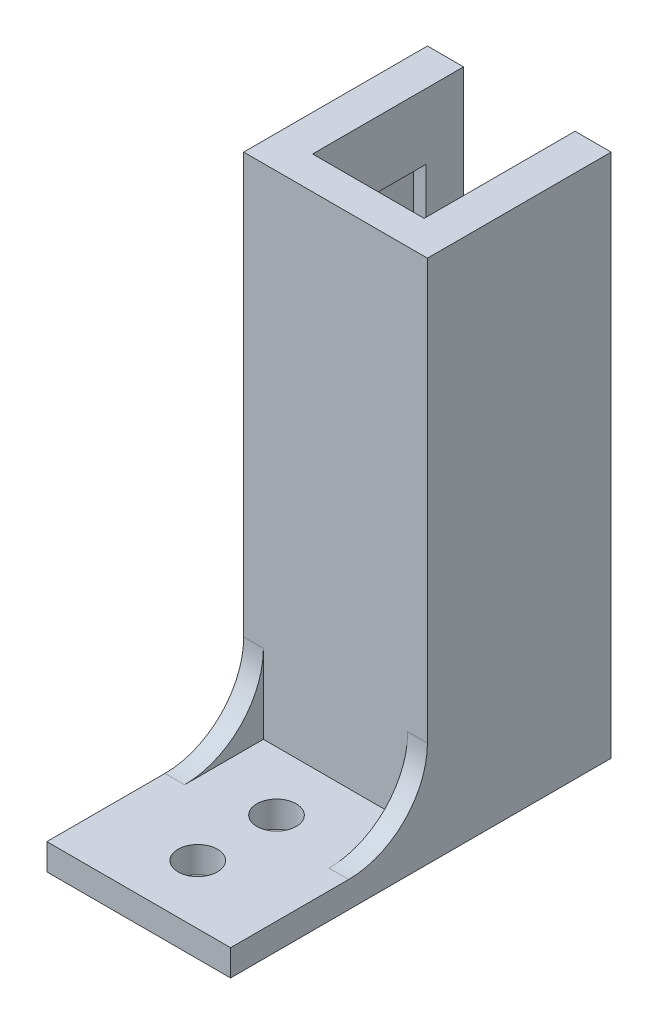
SolidWorks part; units mm, degrees
ref_plane "Front Plane" through (0, 0, 0) normal (0, 0, 1) x (1, 0, 0)
ref_plane "Top Plane" through (0, 0, 0) normal (0, 1, 0) x (1, 0, 0)
ref_plane "Right Plane" through (0, 0, 0) normal (1, 0, 0) x (0, 0, -1)
sketch "Sketch1" plane through (0, 0, 0) normal (0, 0, 1) x (1, 0, 0)
  line L1 (7, 20) -> (-7, 20)
  line L2 (7, 20) -> (7, -20)
  line L3 (7, -20) -> (-7, -20)
  line L4 (-7, 20) -> (-7, -20)
  line L5 (7, 20) -> (-7, -20) construction
  line L6 (7, -20) -> (-7, 20) construction
  point P0 (0, 0)
  dimension "D1" = 14
  dimension "D2" = 40
extrude "Boss-Extrude1" add sketch "Sketch1" along normal blind 14
sketch "Sketch2" plane through (0, -20, 0) normal (0, -1, 0) x (1, 0, 0)
  line L1 (5.2, 2.85) -> (-5.2, 2.85)
  line L2 (5.2, 2.85) -> (5.2, 11.5)
  line L3 (5.2, 11.5) -> (-5.2, 11.5)
  line L4 (-5.2, 2.85) -> (-5.2, 11.5)
  line L8 (4.25, 2.85) -> (-4.25, 2.85)
  line L9 (4.25, 2.85) -> (4.25, 0)
  line L10 (4.25, 0) -> (-4.25, 0)
  line L11 (-4.25, 2.85) -> (-4.25, 0)
  point P4 (0, 2.85)
  point P16 (0, 0)
  dimension "D1" = 11.5
  dimension "D2" = 8.65
  dimension "D3" = 10.4
  dimension "D4" = 8.5
extrude "Cut-Extrude1" cut sketch "Sketch2" against normal blind 35
sketch "Sketch3" plane through (0, -20, 0) normal (0, -1, 0) x (1, 0, 0)
  line L0 (0, 18.5) -> (0, 24.5) construction
  line L1 (7, 14) -> (-7, 14)
  line L2 (7, 14) -> (7, 29)
  line L3 (7, 29) -> (-7, 29)
  line L4 (-7, 14) -> (-7, 29)
  circle A0 centre (0, 18.5) radius 1.5
  circle A1 centre (0, 24.5) radius 1.5
  point P10 (0, 21.5)
  point P11 (-7, 21.5)
  point P15 (0, 14)
  dimension "D1" = 3
  dimension "D2" = 6
  dimension "D3" = 4.5
extrude "Boss-Extrude2" add sketch "Sketch3" against normal blind 2
sketch "Sketch4" plane through (-7, 0, 0) normal (-1, 0, 0) x (0, 0, 1)
  line L1 (29, -18) -> (14, -18) construction
  line L2 (14, 20) -> (14, -18) construction
  line L3 (14, -12) -> (14, -18)
  line L4 (14, -18) -> (20, -18)
  arc A0 (20, -18) -> (14, -12) centre (20, -12) cw
  dimension "D1" = 6
extrude "Boss-Extrude3" add sketch "Sketch4" against normal blind 1.5
mirror "Mirror1" about plane through (0, 0, 0) normal (1, 0, 0) of "Boss-Extrude3"
sketch "Sketch5" plane through (0, 15, 0) normal (0, -1, 0) x (1, 0, 0)
  line L0 (5.2, 11.5) -> (-5.2, 11.5) construction
  line L1 (4.25, 0) -> (-4.25, 0)
  line L2 (4.25, 0) -> (4.25, 11.5)
  line L3 (4.25, 11.5) -> (-4.25, 11.5)
  line L4 (-4.25, 0) -> (-4.25, 11.5)
  line L5 (7, 0) -> (4.25, 0) construction
  line L6 (-4.25, 0) -> (4.25, 0) construction
extrude "Cut-Extrude2" cut sketch "Sketch5" against normal through all
sketch "Sketch6" plane through (0, 0, 0) normal (0, 0, -1) x (-1, 0, 0)
  line L0 (-7, 20) -> (-7, -20) construction
  line L1 (-7, 0) -> (7, 0)
  line L2 (-7, 0) -> (-7, -20)
  line L3 (-7, -20) -> (7, -20)
  line L4 (7, 0) -> (7, -20)
extrude "Cut-Extrude3" [suppressed] cut sketch "Sketch6" against normal through all
sketch "Sketch7" plane through (0, -20, 0) normal (0, -1, 0) x (1, 0, 0)
  line L0 (5.2, 2.85) -> (4.25, 2.85)
  line L1 (4.25, 2.85) -> (4.25, 11.5)
  line L2 (5.2, 11.5) -> (-5.2, 11.5) construction
  line L3 (4.25, 11.5) -> (5.2, 11.5)
  line L4 (5.2, 11.5) -> (5.2, 2.85)
  line L5 (0, 11.5) -> (0, 0) construction
  line L6 (-4.25, 11.5) -> (-5.2, 11.5)
  line L7 (-4.25, 2.85) -> (-4.25, 11.5)
  line L8 (-5.2, 2.85) -> (-4.25, 2.85)
  line L9 (-5.2, 11.5) -> (-5.2, 2.85)
extrude "Boss-Extrude4" add sketch "Sketch7" against normal offset from surface (20 mm away) 15 up to face at (-4.725, 15, 7.175)
